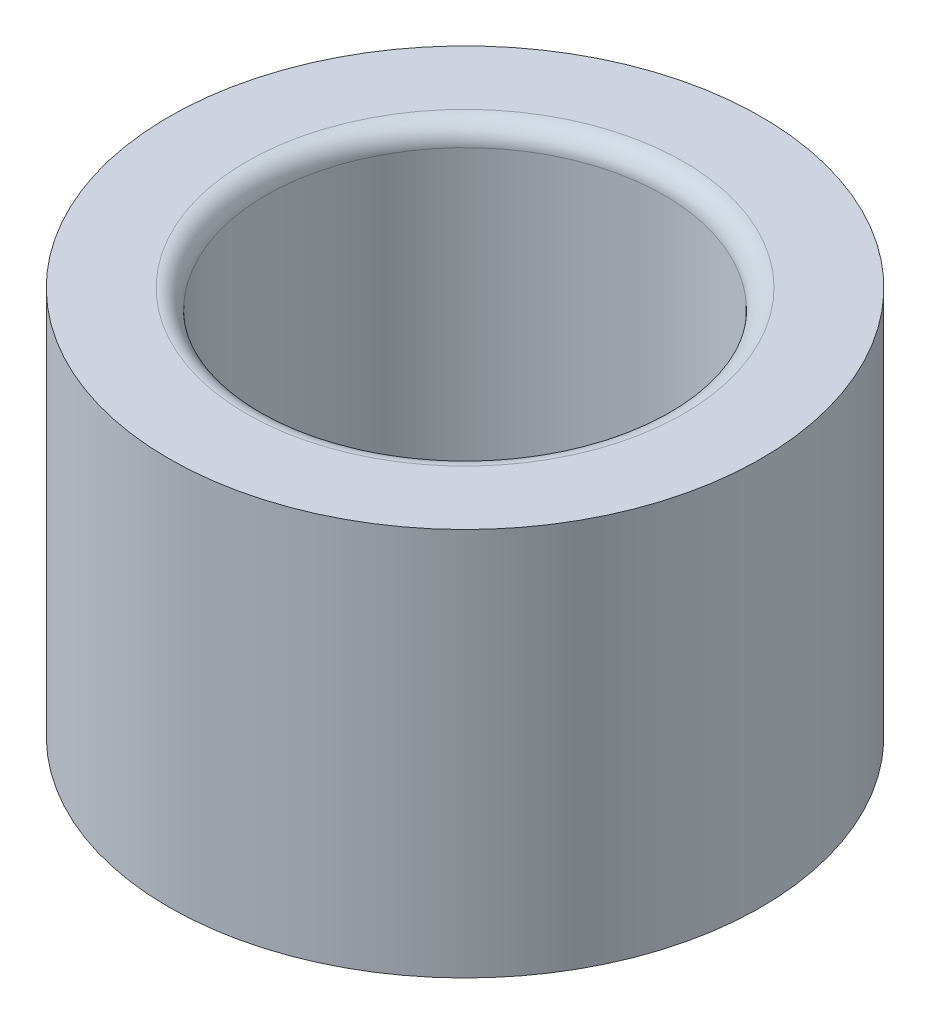
SolidWorks part; units mm, degrees
ref_plane "Front Plane" through (0, 0, 0) normal (0, 0, 1) x (1, 0, 0)
ref_plane "Top Plane" through (0, 0, 0) normal (0, 1, 0) x (1, 0, 0)
ref_plane "Right Plane" through (0, 0, 0) normal (1, 0, 0) x (0, 0, -1)
sketch "Sketch1" plane through (0, 0, 0) normal (0, 1, 0) x (1, 0, 0)
  circle A0 centre (0, 0) radius 10.25
  circle A1 centre (0, 0) radius 15.25
  dimension "D1" = 20.5
  dimension "D2" = 5
extrude "Boss-Extrude1" add sketch "Sketch1" along normal blind 20
fillet "Fillet1" radius 1 1 edges at (0, 20, 10.25)
